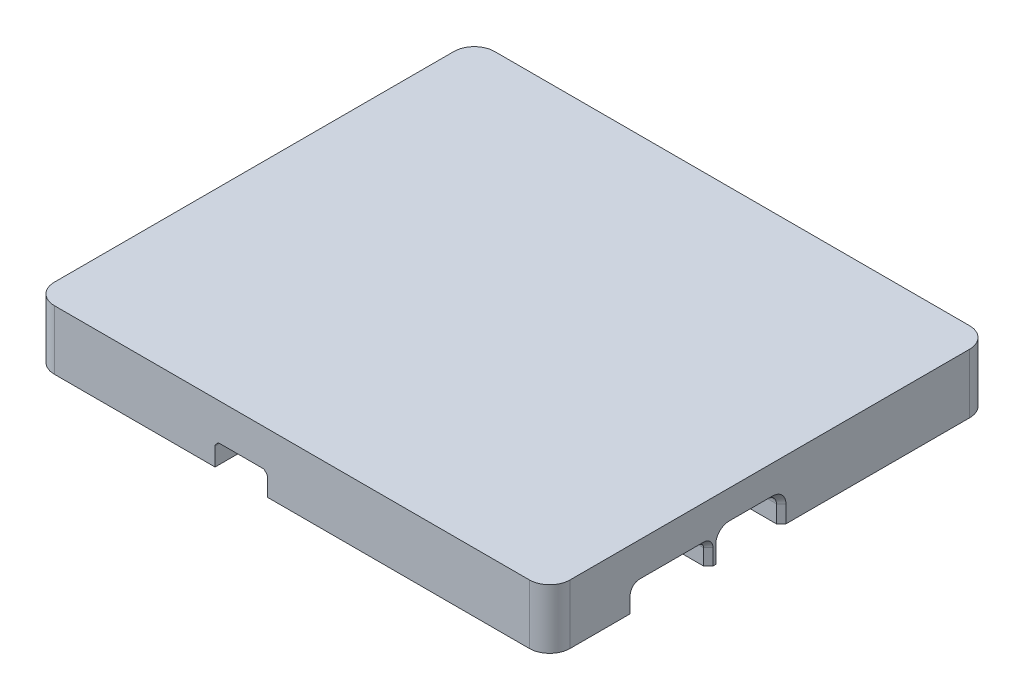
SolidWorks part; units mm, degrees
ref_plane "Front Plane" through (0, 0, 0) normal (0, 0, 1) x (1, 0, 0)
ref_plane "Top Plane" through (0, 0, 0) normal (0, 1, 0) x (1, 0, 0)
ref_plane "Right Plane" through (0, 0, 0) normal (1, 0, 0) x (0, 0, -1)
sketch "Sketch1" plane through (0, 0, 0) normal (0, 1, 0) x (1, 0, 0)
  line L0 (0, 0) -> (8, 0) construction
  line L1 (3, 0) -> (73, 0)
  line L2 (0, 3) -> (0, 57.3265)
  line L4 (76, 3) -> (76, 57.3265)
  line L5 (8, 0) -> (8, 4) construction
  line L6 (38, 0) -> (38, 55.62) construction
  line L7 (0, 30.1633) -> (76, 30.1633) construction
  line L8 (68, 0) -> (68, 4) construction
  line L9 (68, 60.3265) -> (68, 56.3265) construction
  line L10 (76, 61.8826) -> (76, 55.62)
  line L11 (0, 57.3265) -> (0, 55.62)
  line L12 (11, 4) -> (65, 4)
  line L13 (8, 7) -> (8, 53.3265)
  line L14 (11, 56.3265) -> (65, 56.3265)
  line L15 (68, 7) -> (68, 53.3265)
  line L17 (76, 55.62) -> (76, 57.3265)
  line L19 (0, 55.62) -> (0, 61.8826)
  line L20 (3, 64.8826) -> (73, 64.8826)
  arc A0 (8, 7) -> (11, 4) centre (11, 7) ccw
  arc A1 (65, 4) -> (68, 7) centre (65, 7) ccw
  arc A2 (68, 53.3265) -> (65, 56.3265) centre (65, 53.3265) ccw
  arc A3 (11, 56.3265) -> (8, 53.3265) centre (11, 53.3265) ccw
  arc A4 (0, 3) -> (3, 0) centre (3, 3) ccw
  arc A5 (73, 0) -> (76, 3) centre (73, 3) ccw
  arc A8 (3, 64.8826) -> (0, 61.8826) centre (3, 61.8826) ccw
  arc A9 (76, 61.8826) -> (73, 64.8826) centre (73, 61.8826) ccw
  point P32 (76, 0)
  point P38 (0, 55.62)
  dimension "D5" = 3
  dimension "D6" = 3
  dimension "D7" = 3
  dimension "D8" = 3
  dimension "D1" = 55.62
  dimension "D2" = 76
  dimension "D3" = 4
  dimension "D4" = 8
extrude "Boss-Extrude1" add sketch "Sketch1" along normal blind 8.76 contours L10 A9 L20 A8 L19 L2 A4 L1 A5 L4 A3 L14 A2 L15 A1 L12 A0 L13
sketch "Sketch2" plane through (0, 8.76, 0) normal (0, 1, 0) x (1, 0, 0)
  line L0 (8, 48.62) -> (8, 7)
  line L1 (11, 4) -> (65, 4)
  line L2 (68, 7) -> (68, 48.62)
  line L4 (8, 48.62) -> (8, 53.3265)
  line L5 (11, 56.3265) -> (65, 56.3265)
  line L6 (68, 53.3265) -> (68, 48.62)
  arc A0 (8, 7) -> (11, 4) centre (11, 7) ccw
  arc A1 (65, 4) -> (68, 7) centre (65, 7) ccw
  arc A4 (8, 53.3265) -> (11, 56.3265) centre (11, 53.3265) cw
  arc A5 (65, 56.3265) -> (68, 53.3265) centre (65, 53.3265) cw
  dimension "D1" = 3
extrude "Boss-Extrude2" add sketch "Sketch2" against normal blind 0.95
ref_plane "Plane1" through (48.1131, 3.1847, -27.0308) normal (0, 1, 0) x (1, 0, 0)
sketch "Sketch4" plane through (0, 0, 0) normal (-1, 0, 0) x (0, 0, 1)
  line L1 (-34.54, 0) -> (-21.74, 0)
  line L2 (-34.54, 0) -> (-34.54, 6.9)
  line L3 (-34.54, 6.9) -> (-21.74, 6.9)
  line L4 (-21.74, 0) -> (-21.74, 6.9)
  line M11 (-61.8826, 0) -> (-3, 0)
  dimension "D1" = 21.74
  dimension "D2" = 12.8
  dimension "D3" = 6.9
extrude "Cut-Extrude1" cut sketch "Sketch4" against normal up to surface (8 mm away) contours L4 L3 L2 M11 up to face at (8, 3.905, -30.1633)
sketch "Sketch5" plane through (0, 0, 0) normal (0, -1, 0) x (1, 0, 0)
  line L0 (8, -21.74) -> (9.3986, -21.74)
  line L1 (9.3986, -21.74) -> (9.3986, -19.477)
  line L2 (9.3986, -19.477) -> (8, -19.477)
  line L4 (8, -34.54) -> (9.3986, -34.54)
  line L5 (9.3986, -34.54) -> (9.3986, -36.803)
  line L6 (9.3986, -36.803) -> (8, -36.803)
  line L8 (8, -19.477) -> (8, -21.74)
  line L9 (8, -34.54) -> (8, -36.803)
extrude "Boss-Extrude3" add sketch "Sketch5" against normal up to surface (7.81 mm away) up to face at (38, 7.81, -30.1633)
sketch "Sketch6" plane through (76, 0, 0) normal (1, 0, 0) x (0, 0, -1)
  line L0 (12.5534, -0.1) -> (12.5534, 3.0111) construction
  line L2 (23.3596, -0.2) -> (23.3596, 3.2492) construction
  line L4 (12.5534, 0) -> (12.5534, 2.34)
  line L5 (17.9565, 0.84) -> (17.9565, 7.0894) construction
  line L7 (12.5534, 3.04) -> (17.9565, 3.04) construction
  line L8 (13.2534, 3.04) -> (22.6596, 3.04)
  line L9 (23.3596, 0) -> (23.3596, 2.34)
  line L10 (12.5534, 0) -> (23.3596, 0)
  arc A0 (12.5534, 2.34) -> (13.2534, 3.04) centre (13.2534, 2.34) cw
  arc A1 (23.3596, 2.34) -> (22.6596, 3.04) centre (22.6596, 2.34) ccw
  point P7 (12.5534, 0)
  line M14 (3, 0) -> (61.8826, 0)
  dimension "D2" = 0.7
  dimension "D1" = 2.34
extrude "Cut-Extrude2" cut sketch "Sketch6" against normal up to surface (8 mm away) contours L9 A1 L8 A0 L4 M14 up to face at (68, 3.905, -30.1633)
fillet "Fillet1" radius 0.5 2 edges at (4, 6.9, -21.74) (4, 6.9, -34.54)
sketch "Sketch8" plane through (76, 0, 0) normal (1, 0, 0) x (0, 0, -1)
  line L1 (25.17, 0) -> (34.11, 0)
  line L2 (25.17, 0) -> (25.17, 3.85)
  line L3 (25.17, 3.85) -> (34.11, 3.85)
  line L4 (34.11, 0) -> (34.11, 3.85)
  line L5 (0, 8.76) -> (0, 0) construction
  point P4 (0, 0)
  dimension "D1" = 25.17
  dimension "D2" = 8.94
  dimension "D3" = 3.85
extrude "Cut-Extrude6" cut sketch "Sketch8" against normal up to surface (8 mm away) up to face at (68, 2.667, -22.8392)
fillet "Fillet2" radius 1.28 2 edges at (72, 3.85, -34.11) (72, 3.85, -25.17)
sketch "Sketch9" plane through (68, 0, 0) normal (-1, 0, 0) x (0, 0, 1)
  line L0 (-34.11, 0.47) -> (-34.11, 2.57)
  line L1 (-32.83, 3.85) -> (-26.45, 3.85)
  line L2 (-25.17, 2.57) -> (-25.17, 0.47)
  line L3 (-34.76, 0.47) -> (-34.76, 2.57)
  line L4 (-32.83, 4.5) -> (-26.45, 4.5)
  line L5 (-24.52, 2.57) -> (-24.52, 0.47)
  line L8 (-34.11, 0) -> (-34.11, 0.47) construction
  line L9 (-34.11, 0.47) -> (-34.76, 0.47)
  line L10 (-34.11, 0.47) -> (-22.1632, 0.47) construction
  line L11 (-34.76, 0) -> (-34.76, 2.57) construction
  line L12 (-34.11, 0) -> (-34.11, 2.57) construction
  line L13 (-25.17, 0.47) -> (-24.52, 0.47)
  line L15 (-25.17, 2.57) -> (-25.17, 0.2097) construction
  line L16 (-24.52, 2.57) -> (-24.52, 0.2097) construction
  arc A0 (-34.11, 2.57) -> (-32.83, 3.85) centre (-32.83, 2.57) cw
  arc A1 (-26.45, 3.85) -> (-25.17, 2.57) centre (-26.45, 2.57) cw
  arc A2 (-34.76, 2.57) -> (-32.83, 4.5) centre (-32.83, 2.57) cw
  arc A3 (-26.45, 4.5) -> (-24.52, 2.57) centre (-26.45, 2.57) cw
  dimension "D2" = 0.47
  dimension "D1" = 0.65
extrude "Boss-Extrude5" add sketch "Sketch9" along normal blind 1.9
chamfer "Chamfer1" distance 0.7 angle 45 10 edges at (76, 1.17, -23.3596) (76, 1.17, -12.5534) (76, 2.835, -23.1546) (76, 2.835, -12.7584) (76, 3.04, -17.9565) (76, 1.285, -34.11) (76, 3.4751, -33.7351) (76, 3.85, -29.64) (76, 3.4751, -25.5449) (76, 1.285, -25.17)
sketch "Sketch13" plane through (0, 0, 0) normal (0, -1, 0) x (1, 0, 0)
  point P3 (72.387, -49.4322)
sketch "Sketch14" plane through (0, 0, 0) normal (0, -1, 0) x (-1, 0, 0)
  line L1 (-3, 0) -> (-73, 0) construction
  line L2 (0, 3) -> (0, 21.74) construction
  line L3 (-70.8766, 64.8826) -> (-70.8766, 0) construction
  line L4 (-3, 64.8826) -> (-73, 64.8826) construction
  line L5 (-70.8766, 64.8826) -> (-85.0929, 64.8826) construction
  line L6 (-75.8314, 64.8826) -> (-75.8314, 32.4426) construction
  line L7 (-75.8314, 32.4426) -> (26.046, 32.4426) construction
  circle A0 centre (-4.7, 6) radius 1.6
  circle A1 centre (-4.7, 58.8851) radius 1.6
  dimension "D1" = 3.2
  dimension "D2" = 6
  dimension "D3" = 4.7
  dimension "D4" = 32.44
extrude "Cut-Extrude10" cut sketch "Sketch14" against normal blind 6
sketch "Sketch16" plane through (0, 0, 0) normal (0, -1, 0) x (-1, 0, 0)
  line L0 (-76, 11.8534) -> (-76, 3) construction
  line L1 (-3, 0) -> (-73, 0) construction
  line L2 (0, 0) -> (0, 32.44) construction
  line L3 (0, 32.44) -> (-83.1196, 32.44) construction
  circle A0 centre (-71.3, 6) radius 1.6
  circle A1 centre (-71.3, 58.88) radius 1.6
  dimension "D1" = 3.2
  dimension "D3" = 6
  dimension "D2" = 4.7
  dimension "D4" = 32.44
extrude "Cut-Extrude11" cut sketch "Sketch16" against normal blind 6
sketch "Sketch18" plane through (0, 0, -64.8826) normal (0, 0, -1) x (-1, 0, 0)
  line L1 (-64.5, 2.411) -> (-64.5, -8.411) construction
  line L2 (-64.5, 2.41) -> (-63.6088, 2.41) construction
  line L3 (-63.6088, 3.5303) -> (-63.6088, 1.0303) construction
  line L4 (-63.6088, 2.41) -> (-63.6088, 3.3012) construction
  line L6 (-12.389, 3.3) -> (-63.611, 3.3) construction
  line L7 (-38, 3.3) -> (-38, 12.8175) construction
  line L11 (-64.5839, -0.08) -> (-11.4161, -0.08)
  line L12 (-11.4161, -0.08) -> (-11.42, 2.4101)
  line L13 (-12.3912, 3.3812) -> (-38, 3.38)
  line L14 (-63.6088, 3.3812) -> (-38, 3.38)
  line L15 (-64.5839, -0.08) -> (-64.58, 2.4101)
  arc A2 (-12.3912, 3.3812) -> (-11.42, 2.4101) centre (-12.3912, 2.41) cw
  arc A3 (-63.6088, 3.3812) -> (-64.58, 2.4101) centre (-63.6088, 2.41) ccw
extrude "Cut-Extrude12" cut sketch "Sketch18" against normal blind 0.9 contours L15 A3 L14 L13 A2 L12 L11
sketch "Sketch19" plane through (0, 0, 0) normal (0, 0, 1) x (1, 0, 0)
  line L0 (3, 0) -> (73, 0) construction
  line L1 (26.68, 0) -> (34.38, 0)
  line L2 (26.68, 0) -> (26.68, 3.35)
  line L3 (26.68, 3.35) -> (34.38, 3.35)
  line L4 (34.38, 0) -> (34.38, 3.35)
  line L5 (0, 8.76) -> (0, 0) construction
  dimension "D1" = 26.68
  dimension "D2" = 7.7
  dimension "D3" = 3.35
extrude "Cut-Extrude13" cut sketch "Sketch19" against normal up to surface (4 mm away) up to face at (38, 3.905, -4)
chamfer "Chamfer2" distance 0.5 angle 45 2 edges at (34.38, 3.35, -2) (26.68, 3.35, -2)
fillet "Fillet3" radius 0.4 4 edges at (34.38, 2.85, -2) (33.88, 3.35, -2) (26.68, 2.85, -2) (27.18, 3.35, -2)
